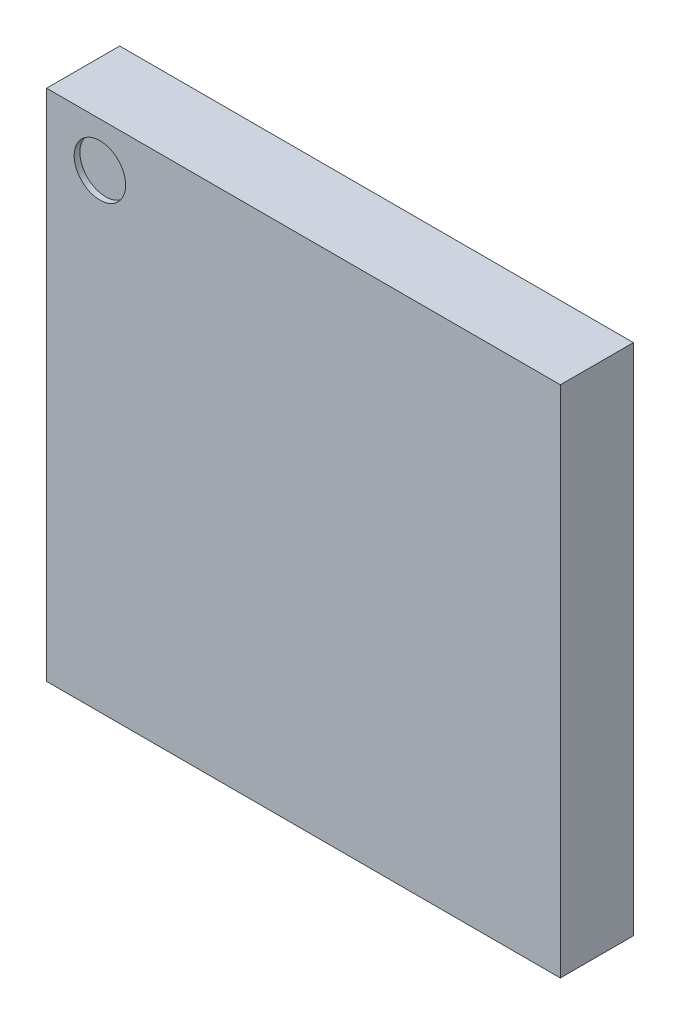
SolidWorks part; units mm, degrees
ref_plane "Front Plane" through (0, 0, 0) normal (0, 0, 1) x (1, 0, 0)
ref_plane "Top Plane" through (0, 0, 0) normal (0, 1, 0) x (1, 0, 0)
ref_plane "Right Plane" through (0, 0, 0) normal (1, 0, 0) x (0, 0, -1)
sketch "Sketch1" plane through (0, 0, 0) normal (0, 0, 1) x (1, 0, 0)
  line L1 (-2.25, -2.25) -> (2.25, -2.25)
  line L2 (-2.25, -2.25) -> (-2.25, 2.25)
  line L3 (-2.25, 2.25) -> (2.25, 2.25)
  line L4 (2.25, -2.25) -> (2.25, 2.25)
  line L5 (-2.25, -2.25) -> (2.25, 2.25) construction
  line L6 (-2.25, 2.25) -> (2.25, -2.25) construction
  point P0 (0, 0)
  dimension "D1" = 4.5
  dimension "D2" = 4.5
extrude "Boss-Extrude1" add sketch "Sketch1" along normal blind 0.64 from offset 0.11
ref_plane "Plane1" through (0, 2, 0) normal (0, 1, 0) x (1, 0, 0)
sketch "Sketch2" plane through (0, 2, 0) normal (0, 1, 0) x (1, 0, 0)
  line L0 (-2, 0) -> (-1.4806, 0) construction
  line L1 (-2.25, -0.75) -> (-2.25, -0.11) construction
  line L2 (-2, -0.125) -> (-2, 0)
  line L3 (-2, -0.125) -> (-1.875, -0.125)
  arc A0 (-1.875, -0.125) -> (-2, 0) centre (-2, -0.125) ccw
  dimension "D1" = 0.25
  dimension "D2" = 0.25
revolve "Revolve1" add sketch "Sketch2" angle 360 about L2
pattern_linear "LPattern1" count 9 spacing 0.5 along (1, 0, 0) count 9 spacing 0.5 along (0, -1, 0) of "Revolve1"
sketch "Sketch3" plane through (0, 0, 0.75) normal (0, 0, 1) x (1, 0, 0)
  circle A0 centre (-1.7831, 1.8601) radius 0.2253
extrude "Cut-Extrude1" cut sketch "Sketch3" against normal blind 0.05
